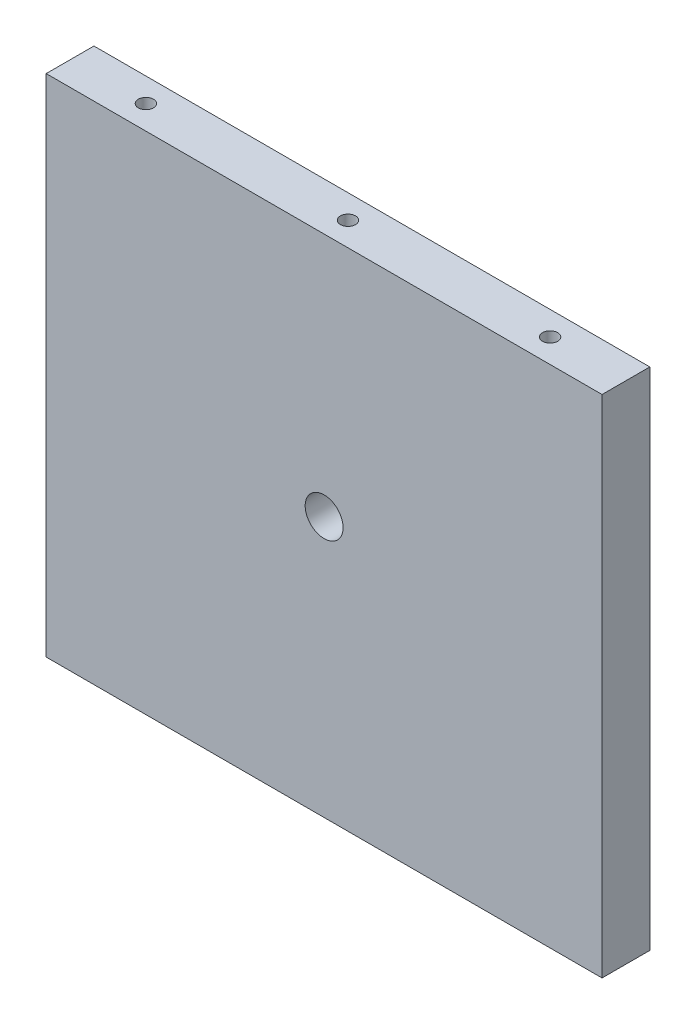
SolidWorks part; units mm, degrees
ref_plane "Front Plane" through (0, 0, 0) normal (0, 0, 1) x (1, 0, 0)
ref_plane "Top Plane" through (0, 0, 0) normal (0, 1, 0) x (1, 0, 0)
ref_plane "Right Plane" through (0, 0, 0) normal (1, 0, 0) x (0, 0, -1)
sketch "Sketch1" plane through (0, 0, 0) normal (0, 0, 1) x (1, 0, 0)
  line L1 (-69.85, 76.2) -> (69.85, 76.2)
  line L2 (-69.85, 76.2) -> (-69.85, -50.8)
  line L3 (-69.85, -50.8) -> (69.85, -50.8)
  line L4 (69.85, 76.2) -> (69.85, -50.8)
  line L5 (-69.85, 76.2) -> (69.85, -50.8) construction
  line L6 (-69.85, -50.8) -> (69.85, 76.2) construction
  circle A0 centre (0, 14.67) radius 4.7625
  point P0 (0, 14.67)
  dimension "D3" = 9.525
  dimension "D1" = 139.7
  dimension "D2" = 127
  dimension "D4" = 65.47
extrude "Boss-Extrude1" add sketch "Sketch1" along normal blind 12
sketch "Sketch2" plane through (0, -50.8, 0) normal (0, -1, 0) x (1, 0, 0)
  line L0 (-69.85, 6) -> (69.85, 6) construction
  line L1 (-69.85, 12) -> (-69.85, 0) construction
  line L2 (69.85, 12) -> (69.85, 0) construction
  point P6 (-50.8, 6)
  point P7 (0, 6)
  point P8 (50.8, 6)
  dimension "D1" = 19.05
  dimension "D2" = 19.05
hole_wizard "Tap Drill for #10-24 Tap1" positions "Sketch3" profile "Sketch4" hole size "#10-24" standard "ANSI Inch"
sketch "Sketch3" plane through (0, -50.8, 0) normal (0, -1, 0) x (-1, 0, 0)
  line L0 (69.85, -6) -> (-69.85, -6) construction
  point P0 (-50.8, -6)
  point P3 (0, -6)
  point P7 (50.8, -6)
sketch "Sketch4" plane through (50.8, -50.8, 6) normal (1, 0, 0) x (0, 0, -1)
  line L0 (0, 0) -> (0, 13.8408)
  line L1 (0, 13.8408) -> (1.8986, 12.7)
  line L2 (1.8986, 12.7) -> (1.8986, 0)
  line L5 (1.8986, 0) -> (0, 0)
  line L10 (0, 13.8408) -> (-1.8987, 12.7) construction
  line L11 (0, -6.35) -> (0, 107.95) construction
  dimension "Hole Dia." = 3.7973
  dimension "Hole Depth" = 12.7
  dimension "Drill Angle" = 118
ref_plane "Plane1" through (0, 12.7, 0) normal (0, -1, 0) x (-1, 0, 0)
mirror "Mirror1" about plane through (0, 12.7, 0) normal (0, -1, 0) of "Tap Drill for #10-24 Tap1"
